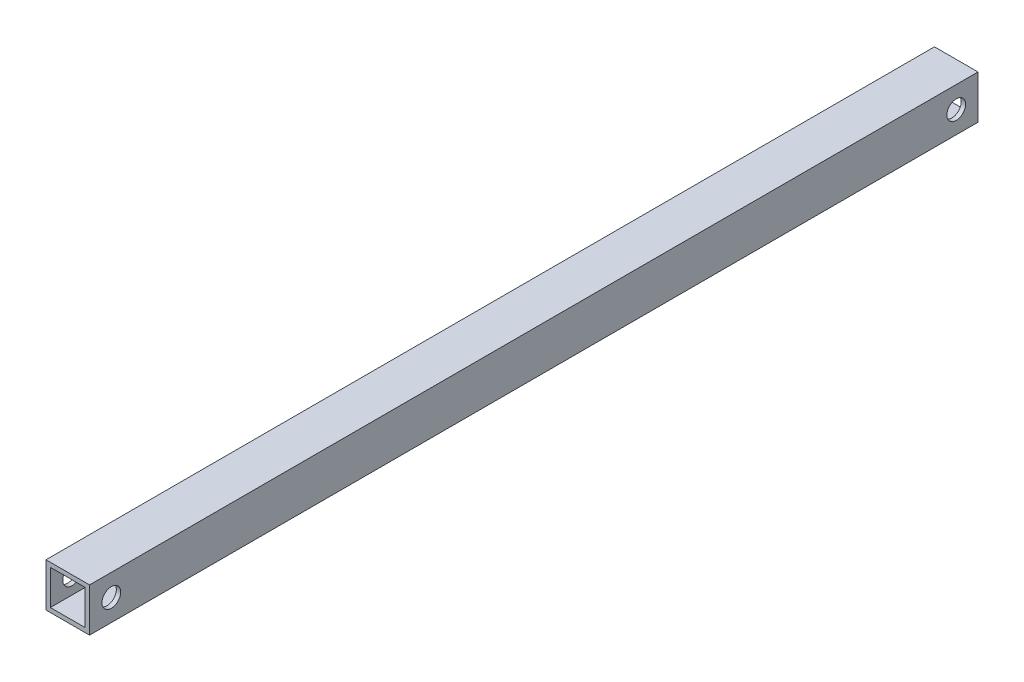
SolidWorks part; units mm, degrees
material "5052-H34"
ref_plane "正面" through (0, 0, 0) normal (0, 0, 1) x (1, 0, 0)
ref_plane "平面" through (0, 0, 0) normal (0, 1, 0) x (1, 0, 0)
ref_plane "右側面" through (0, 0, 0) normal (1, 0, 0) x (0, 0, -1)
sketch "ｽｹｯﾁ1" plane through (0, 0, 0) normal (0, 0, 1) x (1, 0, 0)
  line L1 (-5, 5) -> (5, 5)
  line L2 (-5, 5) -> (-5, -5)
  line L3 (-5, -5) -> (5, -5)
  line L4 (5, 5) -> (5, -5)
  line L5 (-5, 5) -> (5, -5) construction
  line L6 (-5, -5) -> (5, 5) construction
  point P0 (0, 0)
  dimension "D1" = 10
  dimension "D2" = 10
extrude "押し出し-薄板1" add sketch "ｽｹｯﾁ1" along normal blind 204 thin
sketch "ｽｹｯﾁ2" plane through (5, 0, 0) normal (1, 0, 0) x (0, 0, -1)
  line L0 (-102, 5) -> (-102, -5) construction
  line L1 (-204, 5) -> (0, 5) construction
  line L2 (-204, -5) -> (0, -5) construction
  line L3 (0, 0) -> (-5, 0) construction
  circle A0 centre (-5, 0) radius 2.15
  circle A1 centre (-199, 0) radius 2.15
  dimension "D1" = 4.3
  dimension "D2" = 5
extrude "ｶｯﾄ - 押し出し1" cut sketch "ｽｹｯﾁ2" against normal through all
